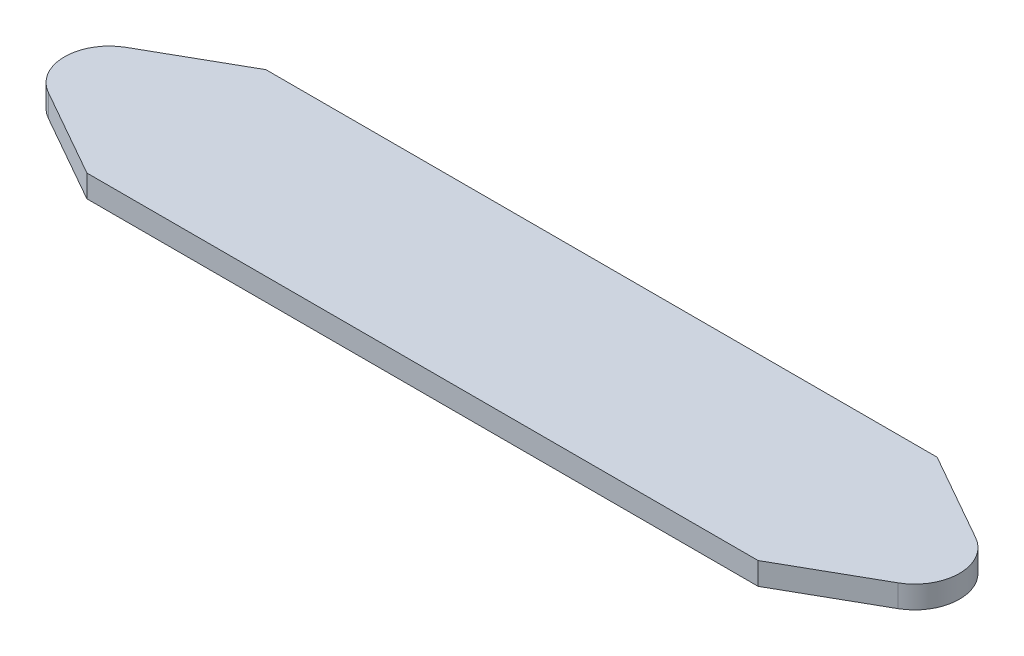
SolidWorks part; units mm, degrees
material "Q355"
ref_plane "前视基准面" through (0, 0, 0) normal (0, 0, 1) x (1, 0, 0)
ref_plane "上视基准面" through (0, 0, 0) normal (0, 1, 0) x (1, 0, 0)
ref_plane "右视基准面" through (0, 0, 0) normal (1, 0, 0) x (0, 0, -1)
sketch "草图1" plane through (0, 0, 0) normal (0, 1, 0) x (1, 0, 0)
  line L0 (-189.8642, 17.3982) -> (-150, 40)
  line L1 (-150, 40) -> (150, 40)
  line L2 (150, 40) -> (189.8642, 17.3982)
  line L3 (-189.8642, -17.3982) -> (-150, -40)
  line L4 (-150, -40) -> (150, -40)
  line L5 (150, -40) -> (189.8642, -17.3982)
  line L6 (-180, 0) -> (180, 0) construction
  arc A0 (-189.8642, 17.3982) -> (-189.8642, -17.3982) centre (-180, 0) ccw
  arc A1 (189.8642, -17.3982) -> (189.8642, 17.3982) centre (180, 0) ccw
  dimension "D3" = 360
  dimension "D4" = 20
  dimension "D1" = 40
  dimension "D2" = 300
extrude "凸台-拉伸1" add sketch "草图1" along normal blind 10
